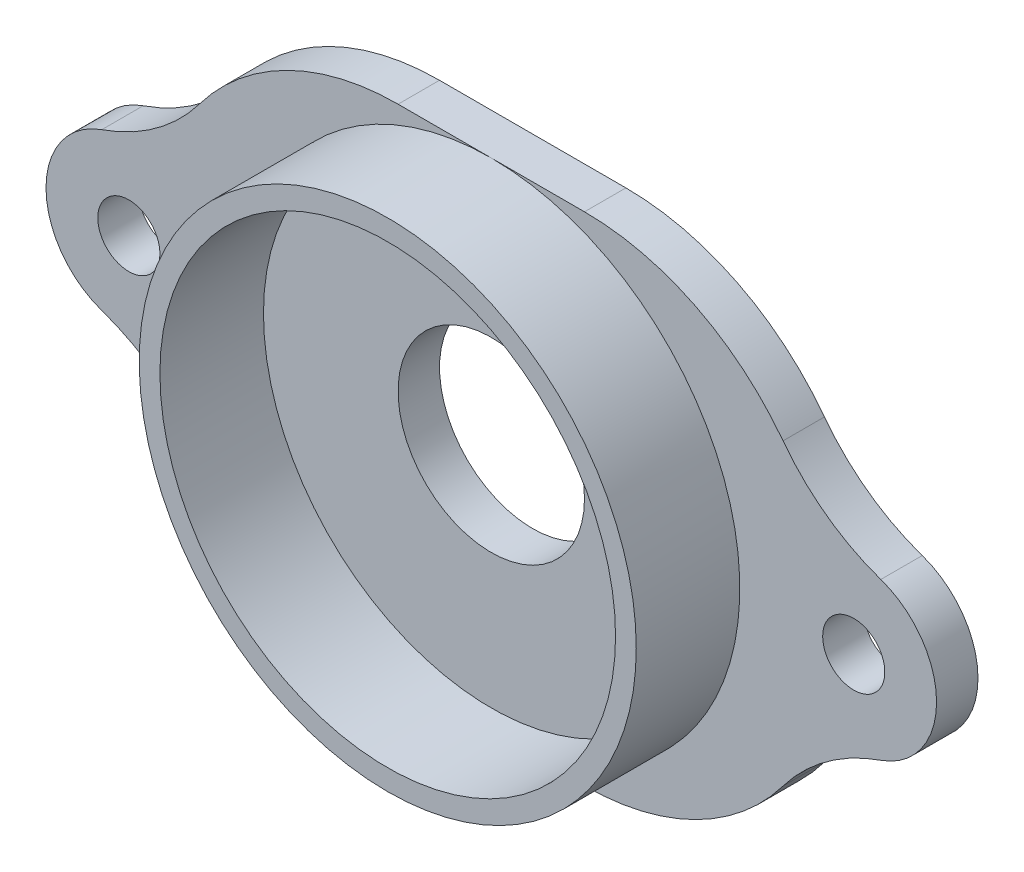
SolidWorks part; units mm, degrees
ref_plane "前视基准面" through (0, 0, 0) normal (0, 0, 1) x (1, 0, 0)
ref_plane "上视基准面" through (0, 0, 0) normal (0, 1, 0) x (1, 0, 0)
ref_plane "右视基准面" through (0, 0, 0) normal (1, 0, 0) x (0, 0, -1)
sketch "草图2" plane through (0, 0, 0) normal (0, 0, 1) x (1, 0, 0)
  line L0 (0, 0) -> (23.5174, 0) construction
  line L1 (0, 0) -> (0, 15) construction
  line L8 (-4.5, 12) -> (4.5, 12)
  line L9 (-4.5, -12) -> (4.5, -12)
  arc A0 (4.5, 12) -> (14.0874, 7.2168) centre (4.5, 0) cw
  arc A1 (18.8077, -3.7802) -> (18.8077, 3.7802) centre (17.5, 0) ccw
  arc A2 (14.0874, 7.2168) -> (18.8077, 3.7802) centre (22.0769, 13.2307) ccw
  arc A3 (-14.0874, 7.2168) -> (-18.8077, 3.7802) centre (-22.0769, 13.2307) cw
  arc A4 (-4.5, 12) -> (-14.0874, 7.2168) centre (-4.5, 0) ccw
  arc A5 (14.0874, -7.2168) -> (18.8077, -3.7802) centre (22.0769, -13.2307) cw
  arc A6 (4.5, -12) -> (14.0874, -7.2168) centre (4.5, 0) ccw
  arc A7 (-4.5, -12) -> (-14.0874, -7.2168) centre (-4.5, 0) cw
  arc A8 (-14.0874, -7.2168) -> (-18.8077, -3.7802) centre (-22.0769, -13.2307) ccw
  arc A9 (-18.8077, -3.7802) -> (-18.8077, 3.7802) centre (-17.5, 0) cw
  point P22 (0, 7.5)
  dimension "D2" = 8
  dimension "D6" = 12
  dimension "D7" = 10
  dimension "D4" = 17.5
extrude "凸台-拉伸2" add sketch "草图2" along normal mid plane 2 contours A4 A3 A9 A8 A7 L9 A6 A5 A1 A2 A0 L8
sketch "草图3" plane through (0, 0, 1) normal (0, 0, 1) x (1, 0, 0)
  line L0 (-4.5, -12) -> (4.5, -12) construction
  circle A0 centre (0, 0) radius 11
  circle A1 centre (0, 0) radius 12
  dimension "D1" = 22
extrude "凸台-拉伸3" add sketch "草图3" along normal blind 5
sketch "草图4" plane through (0, 0, 1) normal (0, 0, 1) x (1, 0, 0)
  circle A0 centre (0, 0) radius 4.5
  dimension "D1" = 9
extrude "切除-拉伸1" cut sketch "草图4" against normal through all
sketch "草图5" plane through (0, 0, -1) normal (0, 0, -1) x (-1, 0, 0)
  circle A0 centre (17.5, 0) radius 1.5
  circle A1 centre (-17.5, 0) radius 1.5
  dimension "D1" = 3
  dimension "D2" = 3
extrude "切除-拉伸2" cut sketch "草图5" against normal through all
